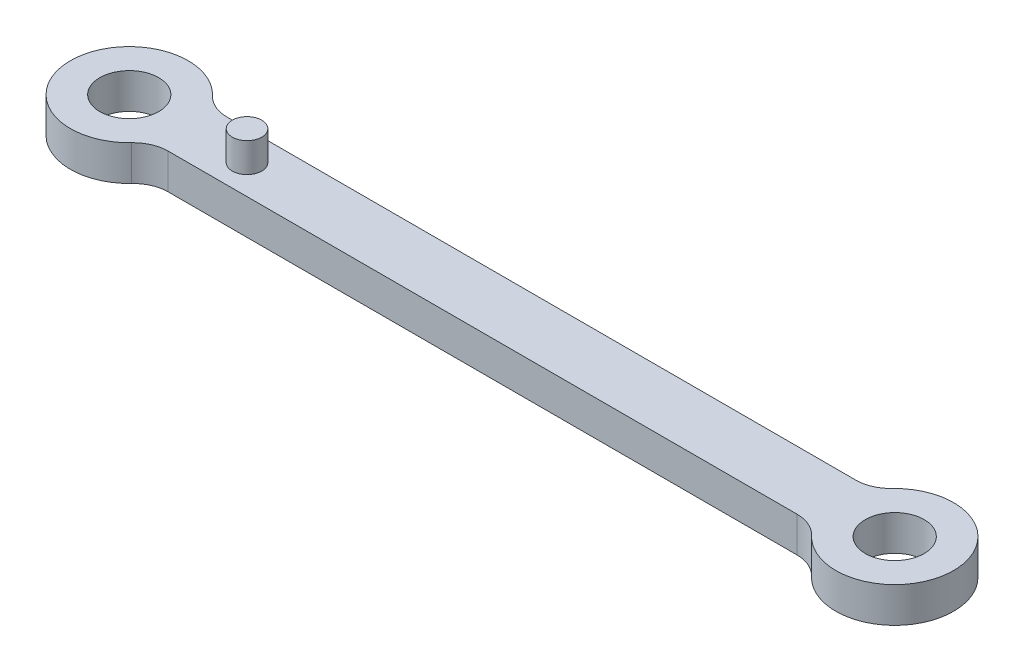
SolidWorks part; units mm, degrees
ref_plane "前视基准面" through (0, 0, 0) normal (0, 0, 1) x (1, 0, 0)
ref_plane "上视基准面" through (0, 0, 0) normal (0, 1, 0) x (1, 0, 0)
ref_plane "右视基准面" through (0, 0, 0) normal (1, 0, 0) x (0, 0, -1)
sketch "草图1" plane through (0, 0, 0) normal (0, 1, 0) x (1, 0, 0)
  line L0 (0, 0) -> (0, -5)
  line L2 (0, -5) -> (130, -5)
  line L3 (0, -5) -> (0, 5)
  line L4 (0, 5) -> (130, 5)
  line L5 (130, -5) -> (130, 5)
  circle A0 centre (0, 0) radius 10
  circle A1 centre (130, 0) radius 10
  dimension "D1" = 20
  dimension "D5" = 20
  dimension "D2" = 5
  dimension "D3" = 10
  dimension "D4" = 130
extrude "凸台-拉伸1" add sketch "草图1" along normal blind 6 contours L4 A0 L2 L0 L3 | A1 L4 A0 L2 | L2 A0 L4 L3 L0 | L4 A1 L2 L5 | L2 A1 L4 L5
fillet "圆角1" radius 6 4 edges at (8.6603, 3, -5) (121.3397, 3, -5) (121.3397, 3, 5) (8.6603, 3, 5)
sketch "草图2" plane through (0, 6, 0) normal (0, 1, 0) x (1, 0, 0)
  line L2 (118.381, 5) -> (11.619, 5)
  line L3 (11.619, -5) -> (118.381, -5)
  line L4 (118.381, 5) -> (11.619, 5)
  line L5 (11.619, -5) -> (118.381, -5)
  circle A0 centre (0, 0) radius 5
  circle A1 centre (130, 0) radius 5
  arc A6 (7.2618, 6.875) -> (11.619, 5) centre (11.619, 11) ccw
  arc A7 (7.2618, 6.875) -> (7.2618, -6.875) centre (0, 0) ccw
  arc A8 (11.619, -5) -> (7.2618, -6.875) centre (11.619, -11) ccw
  arc A9 (122.7382, -6.875) -> (118.381, -5) centre (118.381, -11) ccw
  arc A10 (122.7382, -6.875) -> (122.7382, 6.875) centre (130, 0) ccw
  arc A11 (118.381, 5) -> (122.7382, 6.875) centre (118.381, 11) ccw
  arc A12 (7.2618, 6.875) -> (11.619, 5) centre (11.619, 11) ccw
  arc A13 (7.2618, 6.875) -> (7.2618, -6.875) centre (0, 0) ccw
  arc A14 (11.619, -5) -> (7.2618, -6.875) centre (11.619, -11) ccw
  arc A15 (122.7382, -6.875) -> (118.381, -5) centre (118.381, -11) ccw
  arc A16 (122.7382, -6.875) -> (122.7382, 6.875) centre (130, 0) ccw
  arc A17 (118.381, 5) -> (122.7382, 6.875) centre (118.381, 11) ccw
  dimension "D2" = 10
  dimension "D3" = 10
  dimension "D1" = 0
extrude "切除-拉伸1" cut sketch "草图2" against normal blind 6 contours A0 | A1
sketch "草图3" plane through (0, 6, 0) normal (0, 1, 0) x (1, 0, 0)
  line L0 (0, 0) -> (20, 0)
  line L2 (118.381, 5) -> (11.619, 5)
  line L3 (11.619, -5) -> (118.381, -5)
  line L4 (118.381, 5) -> (11.619, 5)
  line L5 (11.619, -5) -> (118.381, -5)
  circle A0 centre (20, 0) radius 2.5
  arc A6 (7.2618, 6.875) -> (11.619, 5) centre (11.619, 11) ccw
  arc A7 (7.2618, 6.875) -> (7.2618, -6.875) centre (0, 0) ccw
  arc A8 (11.619, -5) -> (7.2618, -6.875) centre (11.619, -11) ccw
  arc A9 (122.7382, -6.875) -> (118.381, -5) centre (118.381, -11) ccw
  arc A10 (122.7382, -6.875) -> (122.7382, 6.875) centre (130, 0) ccw
  arc A11 (118.381, 5) -> (122.7382, 6.875) centre (118.381, 11) ccw
  arc A12 (7.2618, 6.875) -> (11.619, 5) centre (11.619, 11) ccw
  arc A13 (7.2618, 6.875) -> (7.2618, -6.875) centre (0, 0) ccw
  arc A14 (11.619, -5) -> (7.2618, -6.875) centre (11.619, -11) ccw
  arc A15 (122.7382, -6.875) -> (118.381, -5) centre (118.381, -11) ccw
  arc A16 (122.7382, -6.875) -> (122.7382, 6.875) centre (130, 0) ccw
  arc A17 (118.381, 5) -> (122.7382, 6.875) centre (118.381, 11) ccw
  dimension "D3" = 5
  dimension "D2" = 20
  dimension "D1" = 0
extrude "凸台-拉伸2" add sketch "草图3" along normal blind 5
